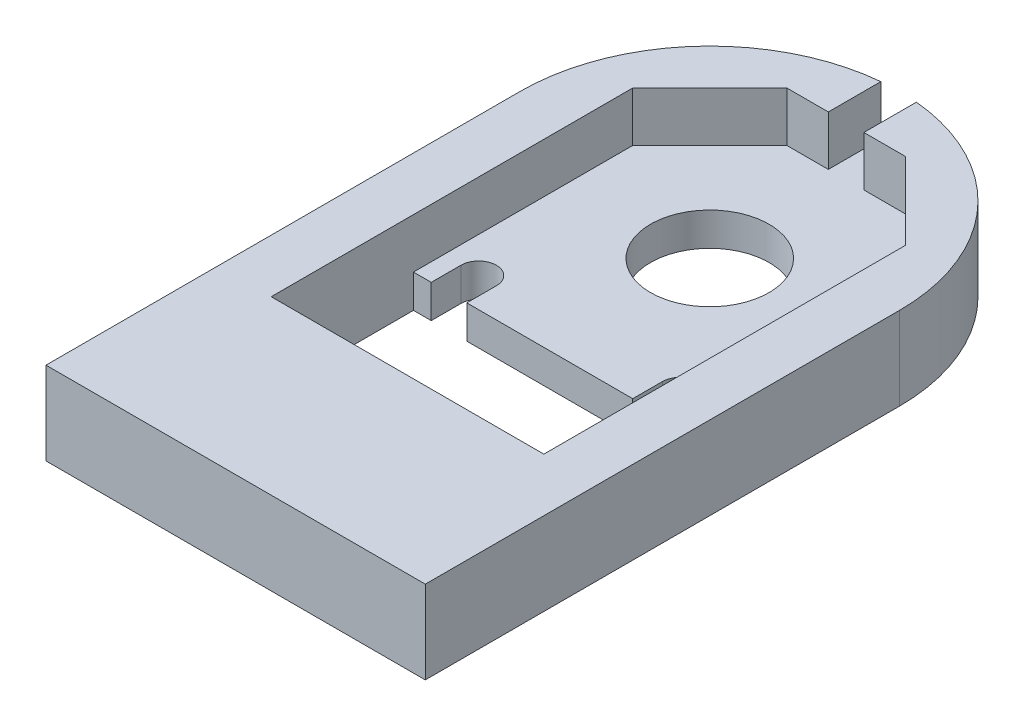
SolidWorks part; units mm, degrees
ref_plane "Front Plane" through (0, 0, 0) normal (0, 0, 1) x (1, 0, 0)
ref_plane "Top Plane" through (0, 0, 0) normal (0, 1, 0) x (1, 0, 0)
ref_plane "Right Plane" through (0, 0, 0) normal (1, 0, 0) x (0, 0, -1)
sketch "Sketch1" plane through (0, 0, 0) normal (0, 1, 0) x (1, 0, 0)
  line L0 (-5.75, -999.648) -> (-5.75, 49000.352) construction
  line L1 (5.75, -999.7466) -> (5.75, 49000.2534) construction
  line L2 (-1004.7888, 5.75) -> (-0.75, 5.75) construction
  line L3 (-1005.0845, -6.75) -> (48994.9155, -6.75) construction
  line L4 (0, 0) -> (0, 5.75) construction
  line L5 (-2.5, 5.75) -> (-0.75, 5.75)
  line L6 (-0.75, 5.75) -> (-0.75, 7.9648)
  line L7 (0.75, 5.75) -> (0.75, 7.9648)
  line L8 (-1002.9652, 2.5) -> (48997.0348, 2.5) construction
  line L9 (-5.75, 2.5) -> (-2.5, 5.75)
  line L10 (2.5, 5.75) -> (5.75, 2.5)
  line L11 (-8, 0) -> (-8, -20)
  line L12 (-8, -20) -> (8, -20)
  line L13 (8, -20) -> (8, 0)
  line L14 (-5.75, 2.5) -> (-5.75, -6.75)
  line L15 (-5.75, -6.75) -> (5.75, -6.75)
  line L16 (5.75, -6.75) -> (5.75, 2.5)
  line L17 (0.75, 5.75) -> (48995.2112, 5.75) construction
  line L18 (0.75, 5.75) -> (2.5, 5.75)
  arc A0 (8, 0) -> (-8, 0) centre (0, 0) ccw
  arc A1 (-0.75, 7.9648) -> (0.75, 7.9648) centre (0, 0) cw
  point P15 (0, 5.75)
  dimension "D1" = 16
  dimension "D2" = 6.75
  dimension "D3" = 11.5
  dimension "D4" = 5.75
  dimension "D5" = 5.75
  dimension "D6" = 5
  dimension "D7" = 0.75
  dimension "D8" = 0.75
  dimension "D9" = 2.5
  dimension "D10" = 20
  dimension "D11" = 2.5
extrude "Boss-Extrude1" add sketch "Sketch1" along normal blind 2.1 contours L13 A0 L7 L18 L10 L16 L15 L14 L9 L5 L6 L11 L12
sketch "Sketch2" plane through (0, 0, 0) normal (0, 1, 0) x (1, 0, 0)
  line L0 (8, 0) -> (8, -20)
  line L1 (8, -20) -> (-8, -20)
  line L2 (-8, -20) -> (-8, 0)
  line L3 (-5.75, 2.5) -> (-5.75, -6.75) construction
  line L4 (5.75, -6.75) -> (5.75, 2.5) construction
  line L6 (-5, -5.5) -> (-5, -6.75)
  line L7 (-5, -6.75) -> (-3.5, -6.75)
  line L8 (-3.5, -6.75) -> (-3.5, -5.5)
  line L9 (3.5, -5.5) -> (3.5, -6.75)
  line L10 (3.5, -6.75) -> (5, -6.75)
  line L11 (5, -6.75) -> (5, -5.5)
  arc A0 (8, 0) -> (-8, 0) centre (0, 0) ccw
  arc A1 (8, 0) -> (-8, 0) centre (0, 0) ccw construction
  circle A2 centre (0, 0) radius 2.5
  arc A3 (-3.5, -5.5) -> (-5, -5.5) centre (-4.25, -5.5) ccw
  arc A4 (5, -5.5) -> (3.5, -5.5) centre (4.25, -5.5) ccw
  dimension "D1" = 5
  dimension "D6" = 1.5
  dimension "D7" = 1.5
  dimension "D2" = 1.5
  dimension "D3" = 1.5
  dimension "D4" = 5.5
  dimension "D5" = 5.5
  dimension "D8" = 1.25
  dimension "D9" = 1.25
extrude "Boss-Extrude2" add sketch "Sketch2" against normal blind 1.4
sketch "Sketch3" plane through (0, 2.1, 0) normal (0, 1, 0) x (1, 0, 0)
  line L0 (-5.75, -6.75) -> (5.75, -6.75)
  line L1 (5.75, -6.75) -> (5.75, -12.75)
  line L2 (5.75, -12.75) -> (-5.75, -12.75)
  line L3 (-5.75, -12.75) -> (-5.75, -6.75)
  dimension "D1" = 6
extrude "Cut-Extrude1" cut sketch "Sketch3" against normal through all
chamfer "Chamfer1" distance 2.5 distance2 4 1 edges at (0, -1.4, 12.75)
